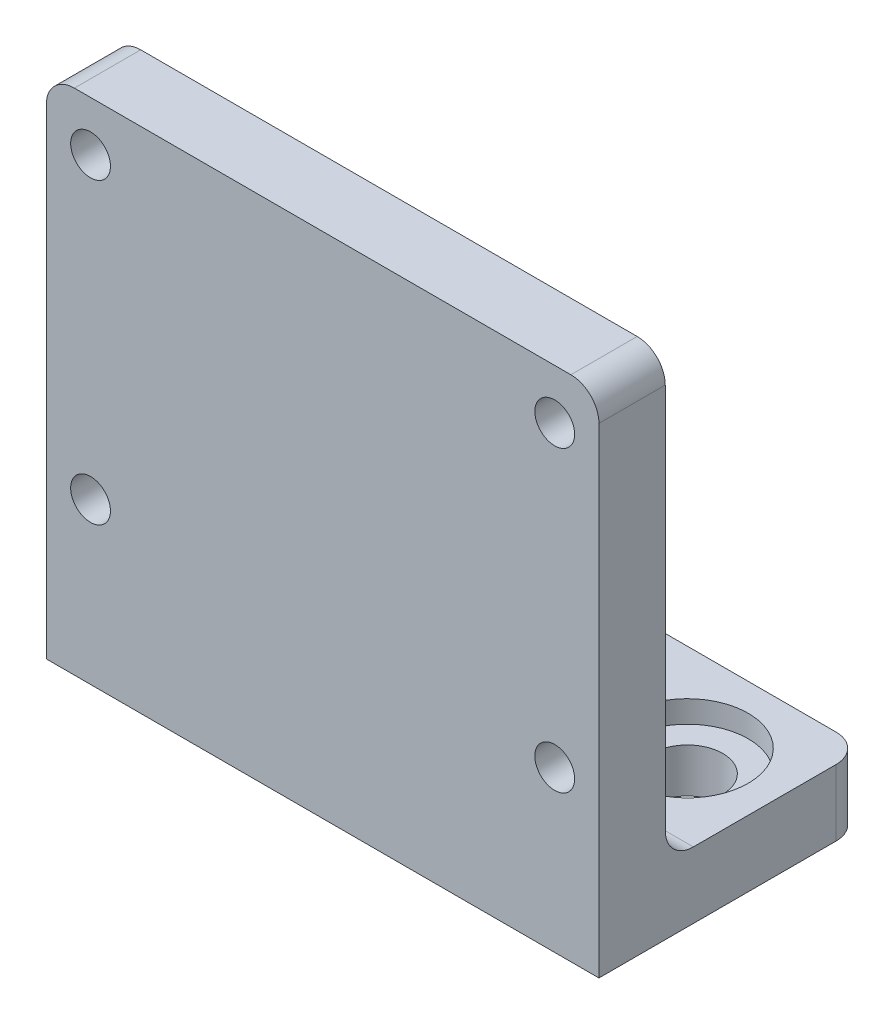
SolidWorks part; units mm, degrees
material "ABS"
ref_plane "Front Plane" through (0, 0, 0) normal (0, 0, 1) x (1, 0, 0)
ref_plane "Top Plane" through (0, 0, 0) normal (0, 1, 0) x (1, 0, 0)
ref_plane "Right Plane" through (0, 0, 0) normal (1, 0, 0) x (0, 0, -1)
sketch "Sketch1" plane through (0, 0, 0) normal (0, 0, 1) x (1, 0, 0)
  line L0 (-12.5, -9) -> (12.5, -9) construction
  line L1 (-10.5, -6.75) -> (10.5, -6.75) construction
  line L2 (-10.5, -6.75) -> (-10.5, 6.75) construction
  line L3 (-10.5, 6.75) -> (10.5, 6.75) construction
  line L4 (10.5, -6.75) -> (10.5, 6.75) construction
  line L5 (-10.5, -6.75) -> (10.5, 6.75) construction
  line L6 (-10.5, 6.75) -> (10.5, -6.75) construction
  line L7 (-12.5, -14) -> (12.5, -14)
  line L8 (-12.5, -14) -> (-12.5, 9)
  line L9 (-12.5, 9) -> (12.5, 9)
  line L10 (12.5, -14) -> (12.5, 9)
  circle A0 centre (-10.5, 6.75) radius 0.9
  circle A1 centre (10.5, 6.75) radius 0.9
  circle A2 centre (10.5, -6.75) radius 0.9
  circle A3 centre (-10.5, -6.75) radius 0.9
  point P0 (0, 0)
  point P14 (0, -14)
  dimension "D5" = 1.8
  dimension "D1" = 21
  dimension "D2" = 13.5
  dimension "D3" = 2
  dimension "D4" = 2.25
  dimension "D6" = 2.25
  dimension "D7" = 5
extrude "Boss-Extrude1" add sketch "Sketch1" against normal blind 3
sketch "Sketch2" plane through (0, 0, 0) normal (1, 0, 0) x (0, 0, -1)
  line L0 (3, 9) -> (12, -11)
  line L1 (12, -11) -> (12, -14)
  line L2 (12, -14) -> (3, -14)
  line L3 (3, -14) -> (3, 9)
  line L4 (0, -14) -> (0, 9) construction
  dimension "D1" = 3
  dimension "D2" = 12
extrude "Boss-Extrude2" add sketch "Sketch2" along normal up to surface and the other way up to surface up to face at (12.5, -2.5, -1.5) other way up to face at (-12.5, -2.5, -1.5)
sketch "Sketch3" plane through (0, 9, 0) normal (0, 1, 0) x (1, 0, 0)
  line L0 (12.5, 12) -> (-12.5, 12) construction
  line L1 (-1, 12) -> (-12.5, 12)
  line L2 (-1, 12) -> (-1, 3)
  line L3 (-1, 3) -> (-12.5, 3)
  line L4 (-12.5, 12) -> (-12.5, 3)
  line L5 (12.5, 3) -> (-12.5, 3) construction
  line L6 (-12.5, 12) -> (-12.5, 3) construction
  line L7 (0, 0) -> (0, 12) construction
  line L8 (12.5, 3) -> (1, 3)
  line L9 (12.5, 3) -> (12.5, 12)
  line L10 (12.5, 12) -> (1, 12)
  line L11 (1, 3) -> (1, 12)
  line L12 (12.5, 0) -> (-12.5, 0) construction
  dimension "D1" = 2
extrude "Cut-Extrude1" cut sketch "Sketch3" against normal up to vertex (20 mm away) up to point (12.5, -11, -12)
sketch "Sketch4" plane through (0, -11, 0) normal (0, 1, 0) x (1, 0, 0)
  line L0 (0, 0) -> (0, 12) construction
  line L1 (12.5, 0) -> (-12.5, 0) construction
  line L2 (1, 12) -> (-1, 12) construction
  line L3 (-12.5, 12) -> (-12.5, 3) construction
  line L4 (-1, 12) -> (-12.5, 12) construction
  circle A0 centre (-8.5, 8) radius 1.6
  circle A1 centre (8.5, 8) radius 1.6
  dimension "D1" = 3.2
  dimension "D2" = 4
  dimension "D3" = 4
extrude "Cut-Extrude2" cut sketch "Sketch4" against normal through all
sketch "Sketch5" plane through (0, -11, 0) normal (0, 1, 0) x (1, 0, 0)
  circle A0 centre (-8.5, 8) radius 2.75
  circle A1 centre (8.5, 8) radius 2.75
  dimension "D1" = 5.5
extrude "Cut-Extrude3" cut sketch "Sketch5" against normal offset from surface (1 mm away) 2 up to face at (-8.5, -14, -6.4)
fillet "Fillet2" radius 1.27 10 edges at (1, -1, -3) (1, -11, -7.5) (6.75, -11, -3) (-1, -1, -3) (-1, -11, -7.5) (-6.75, -11, -3) (-12.5, -12.5, -12) (12.5, -12.5, -12) (-12.5, 9, -1.5) (12.5, 9, -1.5)
equation "\"D6@Sketch1\"=\"D4@Sketch1\""
